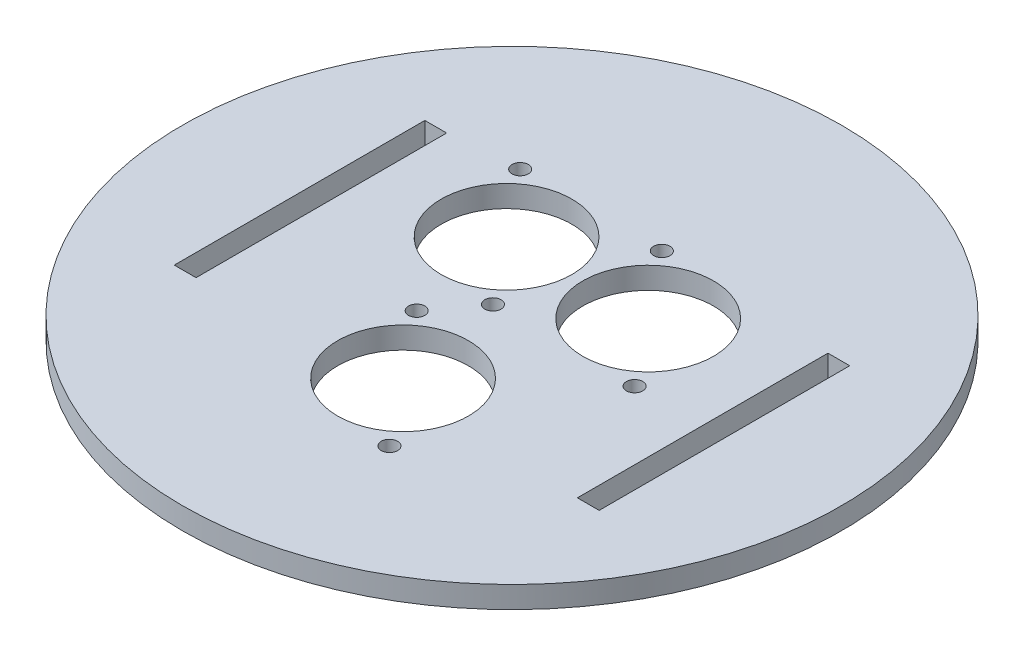
SolidWorks part; units mm, degrees
ref_plane "Front Plane" through (0, 0, 0) normal (0, 0, 1) x (1, 0, 0)
ref_plane "Top Plane" through (0, 0, 0) normal (0, 1, 0) x (1, 0, 0)
ref_plane "Right Plane" through (0, 0, 0) normal (1, 0, 0) x (0, 0, -1)
sketch "Sketch1" plane through (0, 0, 0) normal (0, 1, 0) x (1, 0, 0)
  circle A0 centre (0, 0) radius 60.5
  dimension "D1" = 121
extrude "Boss-Extrude1" add sketch "Sketch1" along normal blind 4
sketch "Sketch2" plane through (0, 4, 0) normal (0, 1, 0) x (1, 0, 0)
  line L0 (0, -20) -> (0, 0)
  line L1 (-13, 12) -> (13, 12) construction
  line L2 (0, 12) -> (0, -20)
  circle A0 centre (0, -20) radius 12
  circle A1 centre (13, 12) radius 12
  circle A2 centre (-13, 12) radius 12
  dimension "D1" = 24
  dimension "D5" = 24
  dimension "D6" = 24
  dimension "D2" = 20
  dimension "D3" = 26
  dimension "D4" = 12
extrude "Cut-Extrude1" cut sketch "Sketch2" against normal blind 4
sketch "Sketch3" plane through (0, 4, 0) normal (0, 1, 0) x (1, 0, 0)
  line L1 (-22.5, 0) -> (-3.5, 0)
  line L2 (-22.5, 0) -> (-22.5, 24)
  line L3 (-22.5, 24) -> (-3.5, 24)
  line L4 (-3.5, 0) -> (-3.5, 24)
  line L5 (-22.5, 0) -> (-3.5, 24) construction
  line L6 (-22.5, 24) -> (-3.5, 0) construction
  line L7 (3.5, 0) -> (22.5, 0)
  line L8 (3.5, 0) -> (3.5, 24)
  line L9 (3.5, 24) -> (22.5, 24)
  line L10 (22.5, 0) -> (22.5, 24)
  line L11 (3.5, 0) -> (22.5, 24) construction
  line L12 (3.5, 24) -> (22.5, 0) construction
  line L13 (-9.5, -32) -> (9.5, -32)
  line L14 (-9.5, -32) -> (-9.5, -8)
  line L15 (-9.5, -8) -> (9.5, -8)
  line L16 (9.5, -32) -> (9.5, -8)
  line L17 (-9.5, -32) -> (9.5, -8) construction
  line L18 (-9.5, -8) -> (9.5, -32) construction
  circle A0 centre (0, -20) radius 12 construction
  circle A1 centre (13, 12) radius 12 construction
  circle A2 centre (-13, 12) radius 12 construction
  circle A3 centre (0, -20) radius 12
  circle A4 centre (13, 12) radius 12
  circle A5 centre (-13, 12) radius 12
  dimension "D1" = 19
  dimension "D2" = 24
  dimension "D3" = 24
  dimension "D4" = 19
hole_wizard "Ø3.0mm Dowel Hole1" positions "3DSketch1" profile "Sketch5" hole size "Ø3.0" standard "ISO" end condition through all
sketch3d "3DSketch1"
  point P0 (-22.5, 4, -24)
  point P3 (-3.5, 4, 0)
  point P6 (3.5, 4, -24)
  point P9 (22.5, 4, 0)
  point P12 (-9.5, 4, 8)
  point P15 (9.5, 4, 32)
sketch "Sketch5" plane through (-22.5, 4, -24) normal (1, 0, 0) x (0, 0, 1)
  line L0 (0, 0) -> (0, 4)
  line L1 (0, 4) -> (1.5, 4)
  line L2 (1.5, 4) -> (1.5, 0)
  line L5 (1.5, 0) -> (0, 0)
  line L11 (0, -6.35) -> (0, 107.95) construction
  dimension "Thru Hole Dia." = 3
  dimension "Thru Hole Depth" = 4
sketch "Sketch6" plane through (0, 4, 0) normal (0, 1, 0) x (1, 0, 0)
  line L0 (-37, 0) -> (0, 0) construction
  line L1 (-39, -23) -> (-35, -23)
  line L2 (-39, -23) -> (-39, 23)
  line L3 (-39, 23) -> (-35, 23)
  line L4 (-35, -23) -> (-35, 23)
  line L5 (-39, -23) -> (-35, 23) construction
  line L6 (-39, 23) -> (-35, -23) construction
  point P0 (-37, 0)
  dimension "D1" = 35
  dimension "D2" = 4
  dimension "D3" = 46
extrude "Cut-Extrude2" cut sketch "Sketch6" against normal blind 4
mirror "Mirror1" about plane through (0, 0, 0) normal (1, 0, 0) of "Cut-Extrude2"
